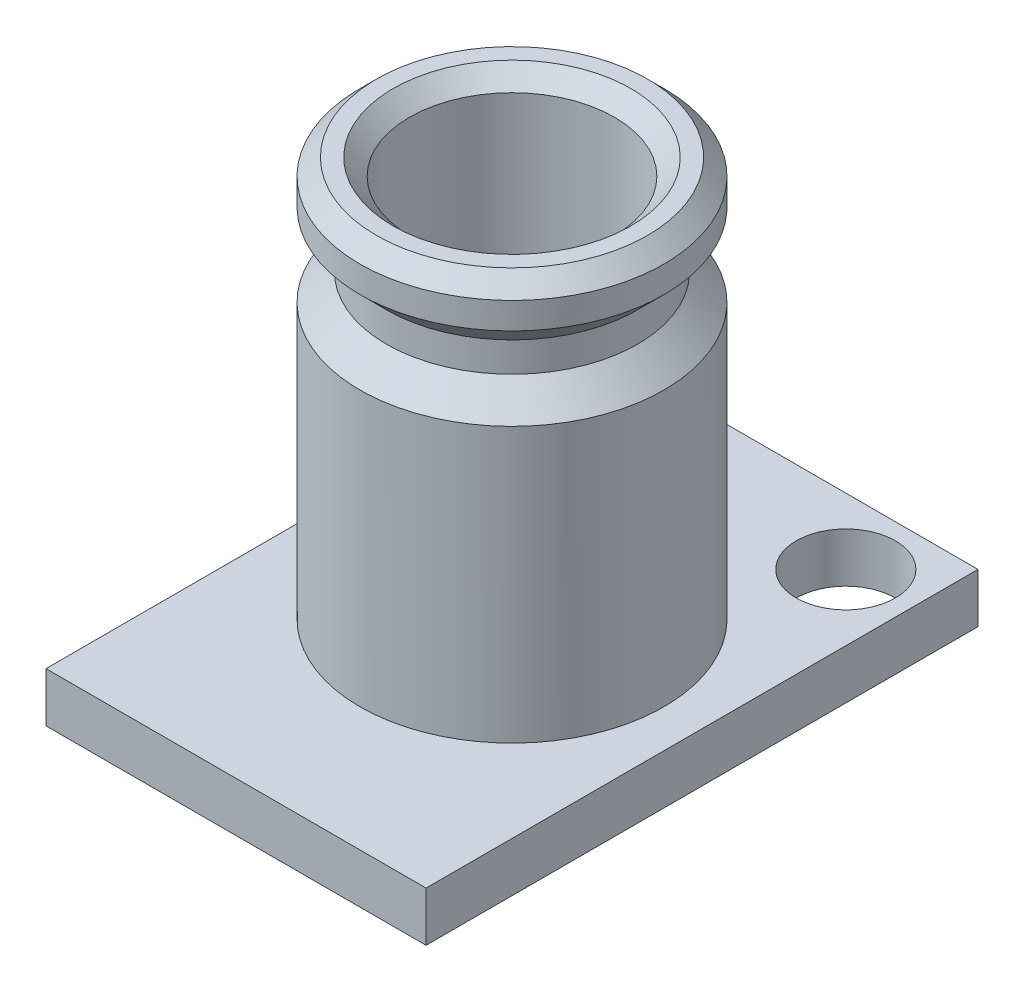
SolidWorks part; units mm, degrees
material "ABS"
ref_plane "Front Plane" through (0, 0, 0) normal (0, 0, 1) x (1, 0, 0)
ref_plane "Top Plane" through (0, 0, 0) normal (0, 1, 0) x (1, 0, 0)
ref_plane "Right Plane" through (0, 0, 0) normal (1, 0, 0) x (0, 0, -1)
sketch "Sketch1" plane through (0, 0, 0) normal (0, 1, 0) x (1, 0, 0)
  line L1 (-5.75, 8.35) -> (5.75, 8.35)
  line L2 (-5.75, 8.35) -> (-5.75, -8.35)
  line L3 (-5.75, -8.35) -> (5.75, -8.35)
  line L4 (5.75, 8.35) -> (5.75, -8.35)
  line L5 (0, -8.35) -> (0, 8.35) construction
  line L6 (-5.75, 0) -> (5.75, 0) construction
  point P0 (0, 0)
  dimension "D1" = 11.5
  dimension "D2" = 16.7
extrude "Boss-Extrude1" add sketch "Sketch1" along normal blind 1.5
sketch "Sketch5" plane through (0, 1.5, 0) normal (0, 1, 0) x (1, 0, 0)
  line L0 (-5.75, 8.35) -> (5.75, 8.35) construction
  line L1 (-5.75, 8.35) -> (-5.75, -8.35) construction
  circle A0 centre (-3.75, 6.35) radius 1.5
  dimension "D1" = 3
  dimension "D2" = 2
  dimension "D3" = 2
extrude "Cut-Extrude2" cut sketch "Sketch5" against normal through all
mirror "Mirror1" about plane through (0, 0, 0) normal (1, 0, 0) of "Cut-Extrude2"
sketch "Sketch2" plane through (0, 1.5, 0) normal (0, 1, 0) x (1, 0, 0)
  line L0 (0, -8.35) -> (0, 8.35) construction
  line L1 (-5.75, 0) -> (5.75, 0) construction
  circle A0 centre (0, 0) radius 4.6
  dimension "D1" = 9.2
extrude "Boss-Extrude2" add sketch "Sketch2" along normal blind 12.1 separate body
chamfer "Chamfer1" distance 0.5 angle 45 1 edges at (0, 13.6, 4.6)
sketch "Sketch3" plane through (0, 0, 0) normal (1, 0, 0) x (0, 0, -1)
  line L0 (4.6, 12.3) -> (3.8, 11.5)
  line L1 (4.6, 1.5) -> (4.6, 13.1) construction
  line L2 (3.8, 11.5) -> (3.8, 10.6)
  line L3 (3.8, 10.6) -> (4.6, 9.8)
  line L4 (4.6, 9.8) -> (4.6, 12.3)
  line L5 (-4.6, 13.1) -> (4.6, 13.1) construction
  line L6 (0, -1000) -> (0, 49000) construction
  dimension "D1" = 45
  dimension "D2" = 0.8
  dimension "D3" = 0.8
  dimension "D4" = 2.5
revolve "Cut-Revolve1" cut sketch "Sketch3" angle 360 about L6
sketch "Sketch4" plane through (0, 13.6, 0) normal (0, 1, 0) x (1, 0, 0)
  circle A0 centre (0, 0) radius 3.1
  circle A1 centre (0, 0) radius 4.6 construction
  dimension "D1" = 1.5
extrude "Cut-Extrude1" cut sketch "Sketch4" against normal blind 8
chamfer "Chamfer2" distance 0.5 angle 45 1 edges at (0, 13.6, 3.1)
